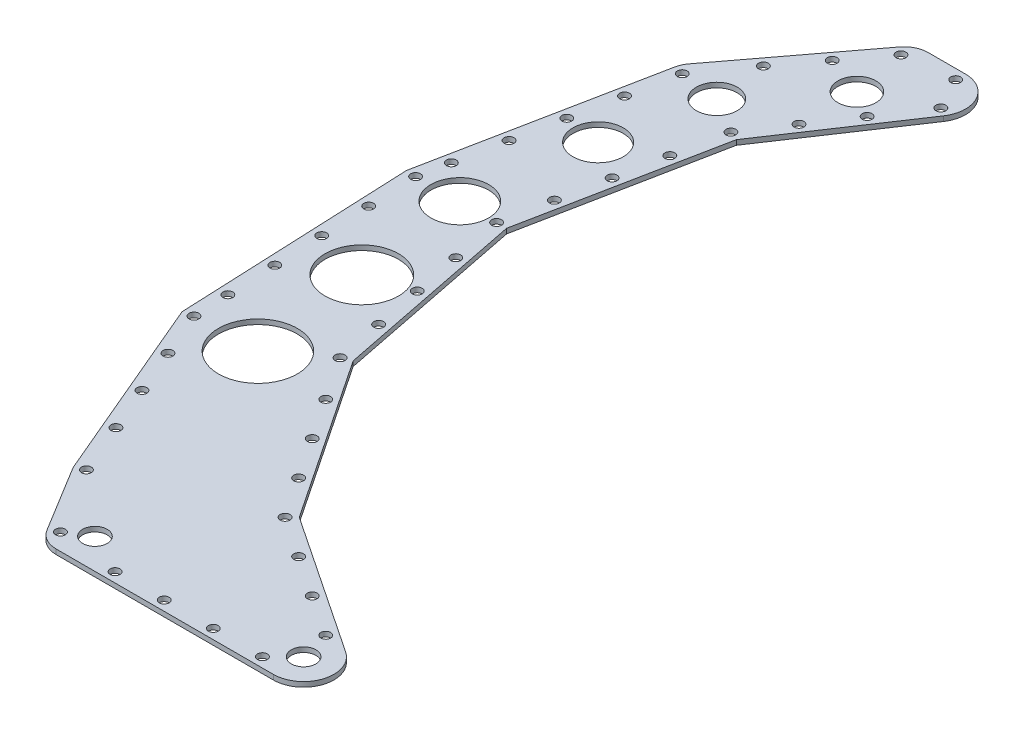
SolidWorks part; units mm, degrees
ref_plane "Front Plane" through (0, 0, 0) normal (0, 0, 1) x (1, 0, 0)
ref_plane "Top Plane" through (0, 0, 0) normal (0, 1, 0) x (1, 0, 0)
ref_plane "Right Plane" through (0, 0, 0) normal (1, 0, 0) x (0, 0, -1)
sketch "Sketch1" [suppressed] plane through (0, 0, 0) normal (0, 1, 0) x (1, 0, 0)
  line L0 (0, 0) -> (-179.6051, 179.6051)
  line L1 (0, 0) -> (179.6051, 179.6051)
  line L2 (0, 0) -> (254, 0) construction
  circle A0 centre (0, 0) radius 254
  dimension "D1" = 45
  dimension "D3" = 508
  dimension "D2" = 90
sketch "Sketch2" plane through (0, 0, 0) normal (0, 1, 0) x (1, 0, 0)
  line L0 (-196.3242, 163.3681) -> (-239.2628, 99.1059)
  line L1 (-238.6954, 182.7217) -> (-285.4443, 120.8311)
  line L2 (-287.7663, 115.6541) -> (-310.7714, 0)
  line L3 (-310.7714, 0) -> (-305.5367, -121.3638)
  line L4 (-305.5367, -121.3638) -> (-263.9493, -219.2687)
  line L5 (-263.9493, -219.2687) -> (-242.6414, -254.121)
  line L6 (-228.5615, 187.7671) -> (-209.3657, 187.7671)
  line L7 (-239.2628, 99.1059) -> (-258.9762, 0)
  line L8 (-258.9762, 0) -> (-239.2628, -99.1059)
  line L9 (-239.2628, -99.1059) -> (-183.1238, -183.1238)
  line L10 (-183.1238, -183.1238) -> (-110.7686, -231.47)
  line L11 (-231.806, -260.1965) -> (-119.4827, -260.1965)
  line L16 (0, -258.9762) -> (49.5529, -249.1195) [skipped]
  line L17 (-49.5529, -249.1195) -> (0, -258.9762) [skipped]
  line L18 (-99.1059, 239.2628) -> (-141.1148, 211.1933) [skipped]
  line L19 (0, 258.9762) -> (-49.5529, 249.1195) [skipped]
  line L20 (141.1148, 211.1933) -> (99.1059, 239.2628) [skipped]
  line L21 (99.1059, 239.2628) -> (0, 258.9762) [skipped]
  line L22 (258.9762, 0) -> (239.2628, 99.1059) [skipped]
  line L23 (239.2628, 99.1059) -> (183.1238, 183.1238) [skipped]
  line L24 (99.1059, -239.2628) -> (183.1238, -183.1238) [skipped]
  line L25 (183.1238, -183.1238) -> (239.2628, -99.1059) [skipped]
  line L26 (239.2628, -99.1059) -> (258.9762, 0) [skipped]
  arc A0 (-242.6414, -254.121) -> (-231.806, -260.1965) centre (-231.806, -247.4965) ccw
  arc A1 (-110.7686, -231.47) -> (-119.4827, -260.1965) centre (-119.4827, -244.5116) cw
  arc A2 (-209.3657, 187.7671) -> (-196.3242, 163.3681) centre (-209.3657, 172.0821) cw
  arc A3 (-285.4443, 120.8311) -> (-287.7663, 115.6541) centre (-275.3104, 113.1765) ccw
  arc A4 (-238.6954, 182.7217) -> (-228.5615, 187.7671) centre (-228.5615, 175.0671) cw
  dimension "D1" = 12.7
  dimension "D2" = 12.7
extrude "Arm" add sketch "Sketch2" along normal blind 2.54
sketch "Sketch3" plane through (0, 2.54, 0) normal (0, 1, 0) x (1, 0, 0)
  circle A0 centre (-262.5645, 112.3177) radius 10.5639
  circle A1 centre (-273.83, 62.1795) radius 12.9986
  circle A2 centre (-283.2107, 0) radius 14.9594
  circle A3 centre (-275.5631, -58.3289) radius 18.9894
  circle A4 centre (-268.2513, -119.3931) radius 20.4143
  circle A7 centre (-229.5339, 151.758) radius 9.8106
extrude "Lighting Holes" cut sketch "Sketch3" against normal up to next
ref_plane "Plane1" through (0, 25.4, 0) normal (0, 1, 0) x (1, 0, 0)
pattern_linear "LPattern5" [suppressed] count 2 spacing 25.4
sketch "Sketch4" plane through (0, 2.54, 0) normal (0, 1, 0) x (1, 0, 0)
  line L0 (-119.4827, -244.5116) -> (-227.4327, -244.5116) construction
  circle A0 centre (-119.4827, -244.5116) radius 6.35
  circle A1 centre (-227.4327, -244.5116) radius 6.35
extrude "Pivot Holes" cut sketch "Sketch4" against normal up to next
sketch "Sketch5" plane through (0, 2.54, 0) normal (0, 1, 0) x (1, 0, 0)
  line L12 (-186.7863, -186.7863) -> (-200.8978, -165.6669) construction
  line L13 (-244.048, -101.088) -> (-249.0033, -76.1761) construction
  line L14 (-264.1557, 0) -> (-259.2004, 24.9119) construction
  line L16 (-244.048, 101.088) -> (-229.9365, 122.2073) construction
  line L18 (-234.6418, 179.6599) -> (-249.9511, 159.392) construction
  line L20 (-282.784, 114.6631) -> (-287.7393, 89.7511) construction
  line L22 (-305.6698, -0.3917) -> (-304.5752, -25.7681) construction
  line L24 (-231.806, -255.1165) -> (-119.4827, -255.1165)
  line L25 (-259.42, -216.9382) -> (-238.3072, -251.4712)
  line L26 (-300.5011, -120.2251) -> (-259.42, -216.9382)
  line L27 (-305.6698, -0.3917) -> (-300.5011, -120.2251)
  line L28 (-282.784, 114.6631) -> (-305.6698, -0.3917)
  line L29 (-234.6418, 179.6599) -> (-281.3907, 117.7693)
  line L30 (-209.3657, 182.6871) -> (-228.5615, 182.6871)
  line L31 (-113.5909, -235.6939) -> (-186.7863, -186.7863)
  line L32 (-186.7863, -186.7863) -> (-244.048, -101.088)
  line L33 (-244.048, -101.088) -> (-264.1557, 0)
  line L34 (-264.1557, 0) -> (-244.048, 101.088)
  line L35 (-244.048, 101.088) -> (-200.548, 166.1903)
  line L36 (-231.806, -255.1165) -> (-119.4827, -255.1165) construction
  line L37 (-259.42, -216.9382) -> (-238.3072, -251.4712) construction
  line L38 (-300.5011, -120.2251) -> (-259.42, -216.9382) construction
  line L39 (-305.6698, -0.3917) -> (-300.5011, -120.2251) construction
  line L40 (-282.784, 114.6631) -> (-305.6698, -0.3917) construction
  line L41 (-234.6418, 179.6599) -> (-281.3907, 117.7693) construction
  line L42 (-209.3657, 182.6871) -> (-228.5615, 182.6871) construction
  line L43 (-113.5909, -235.6939) -> (-186.7863, -186.7863) construction
  line L44 (-186.7863, -186.7863) -> (-244.048, -101.088) construction
  line L45 (-244.048, -101.088) -> (-264.1557, 0) construction
  line L46 (-264.1557, 0) -> (-244.048, 101.088) construction
  line L47 (-244.048, 101.088) -> (-200.548, 166.1903) construction
  line L48 (-300.5011, -120.2251) -> (-290.5706, -143.6034) construction
  line L51 (-186.7863, -186.7863) -> (-165.6669, -200.8978) construction
  circle A5 centre (-186.7863, -186.7863) radius 2.54
  circle A6 centre (-200.8978, -165.6669) radius 2.54
  circle A7 centre (-215.0092, -144.5476) radius 2.54
  circle A8 centre (-229.1207, -123.4283) radius 2.54
  circle A9 centre (-244.048, -101.088) radius 2.54
  arc A10 (-238.3072, -251.4712) -> (-231.806, -255.1165) centre (-231.806, -247.4965) ccw
  arc A11 (-281.3907, 117.7693) -> (-282.784, 114.6631) centre (-275.3104, 113.1765) ccw
  arc A12 (-228.5615, 182.6871) -> (-234.6418, 179.6599) centre (-228.5615, 175.0671) ccw
  arc A13 (-119.4827, -255.1165) -> (-113.5909, -235.6939) centre (-119.4827, -244.5116) ccw
  arc A14 (-200.548, 166.1903) -> (-209.3657, 182.6871) centre (-209.3657, 172.0821) ccw
  arc A15 (-238.3072, -251.4712) -> (-231.806, -255.1165) centre (-231.806, -247.4965) ccw construction
  arc A16 (-281.3907, 117.7693) -> (-282.784, 114.6631) centre (-275.3104, 113.1765) ccw construction
  arc A17 (-228.5615, 182.6871) -> (-234.6418, 179.6599) centre (-228.5615, 175.0671) ccw construction
  arc A18 (-119.4827, -255.1165) -> (-113.5909, -235.6939) centre (-119.4827, -244.5116) ccw construction
  arc A19 (-200.548, 166.1903) -> (-209.3657, 182.6871) centre (-209.3657, 172.0821) ccw construction
  circle A20 centre (-249.0033, -76.1761) radius 2.54
  circle A21 centre (-253.9586, -51.2641) radius 2.54
  circle A22 centre (-258.9139, -26.3522) radius 2.54
  circle A23 centre (-264.1557, 0) radius 2.54
  circle A24 centre (-259.2004, 24.9119) radius 2.54
  circle A25 centre (-254.2451, 49.8239) radius 2.54
  circle A26 centre (-249.2898, 74.7358) radius 2.54
  circle A27 centre (-244.048, 101.088) radius 2.54
  circle A28 centre (-229.9365, 122.2073) radius 2.54
  circle A29 centre (-215.8251, 143.3267) radius 2.54
  circle A30 centre (-200.548, 166.1903) radius 2.54
  circle A31 centre (-209.3657, 182.6871) radius 2.54
  circle A32 centre (-249.9511, 159.392) radius 2.54
  circle A33 centre (-234.6418, 179.6599) radius 2.54
  circle A34 centre (-265.2604, 139.1241) radius 2.54
  circle A35 centre (-282.784, 114.6631) radius 2.54
  circle A36 centre (-287.7393, 89.7511) radius 2.54
  circle A37 centre (-292.6945, 64.8392) radius 2.54
  circle A38 centre (-297.6498, 39.9272) radius 2.54
  circle A39 centre (-302.6051, 15.0153) radius 2.54
  circle A40 centre (-305.6698, -0.3917) radius 2.54
  circle A41 centre (-304.5752, -25.7681) radius 2.54
  circle A42 centre (-303.4807, -51.1445) radius 2.54
  circle A43 centre (-302.3861, -76.5209) radius 2.54
  circle A44 centre (-301.2916, -101.8973) radius 2.54
  circle A45 centre (-300.5011, -120.2251) radius 2.54
  circle A46 centre (-290.5706, -143.6034) radius 2.54
  circle A47 centre (-280.6401, -166.9817) radius 2.54
  circle A48 centre (-270.7097, -190.36) radius 2.54
  circle A49 centre (-259.42, -216.9382) radius 2.54
  circle A50 centre (-238.3072, -251.4712) radius 2.54
  circle A52 centre (-206.406, -255.1165) radius 2.54
  circle A53 centre (-181.006, -255.1165) radius 2.54
  circle A54 centre (-155.606, -255.1165) radius 2.54
  circle A55 centre (-130.206, -255.1165) radius 2.54
  circle A56 centre (-165.6669, -200.8978) radius 2.54
  circle A57 centre (-144.5476, -215.0092) radius 2.54
  circle A58 centre (-123.4283, -229.1207) radius 2.54
  dimension "D2" = 5.08
  dimension "D3" = 4
  dimension "D5" = 4
  dimension "D7" = 4
  dimension "D9" = 3
  dimension "D11" = 5.08
  dimension "D12" = 5.08
  dimension "D13" = 3
  dimension "D14" = 5.08
  dimension "D16" = 5.08
  dimension "D19" = 5.08
  dimension "D22" = 5.08
  dimension "D25" = 5.08
  dimension "D26" = 5.08
  dimension "D4" = 25.4
  dimension "D6" = 25.4
  dimension "D8" = 25.4
  dimension "D10" = 25.4
  dimension "D15" = 25.4
  dimension "D18" = 25.4
  dimension "D21" = 25.4
  dimension "D24" = 25.4
  dimension "D31" = 25.4
  dimension "D1" = 5.08
  dimension "D17" = 5
  dimension "D20" = 5
  dimension "D23" = 4
  dimension "D30" = 4
extrude "Edge Holes" cut sketch "Sketch5" against normal up to next (2.54 mm away)
